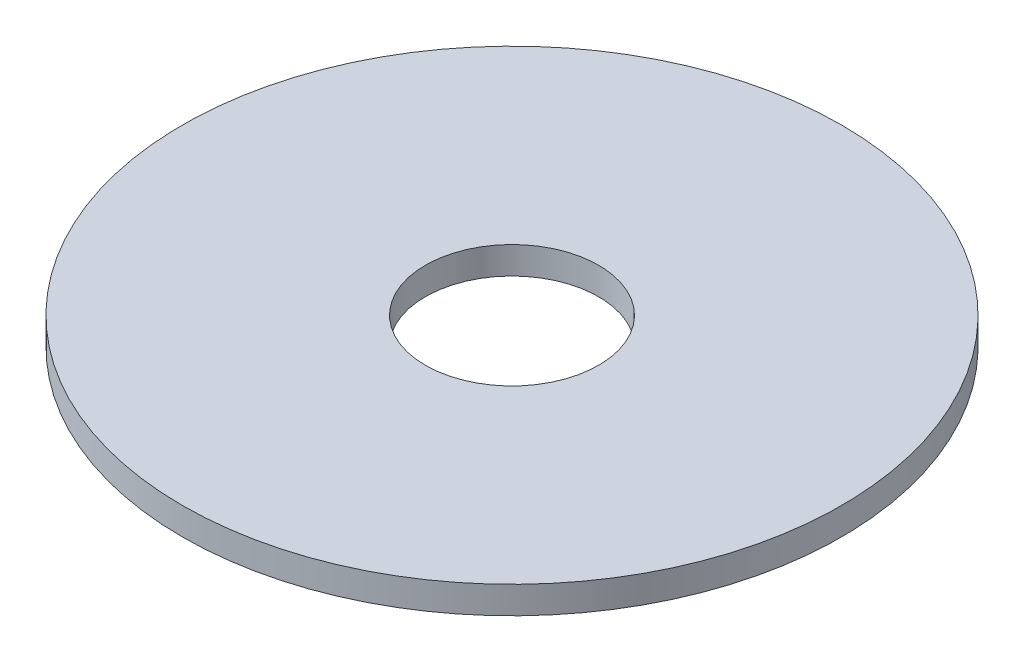
SolidWorks part; units mm, degrees
ref_plane "Front Plane" through (0, 0, 0) normal (0, 0, 1) x (1, 0, 0)
ref_plane "Top Plane" through (0, 0, 0) normal (0, 1, 0) x (1, 0, 0)
ref_plane "Right Plane" through (0, 0, 0) normal (1, 0, 0) x (0, 0, -1)
sketch "Sketch1" plane through (0, 0, 0) normal (0, 1, 0) x (1, 0, 0)
  line L0 (-35.547, 0) -> (35.1572, 0) construction
  line L1 (0, 34.6199) -> (0, -33.3517) construction
  circle A0 centre (0, 0) radius 24.15
  circle A3 centre (0, 0) radius 6.35
  dimension "D1" = 48.3
  dimension "D2" = 12.7
extrude "Boss-Extrude1" add sketch "Sketch1" along normal blind 2
